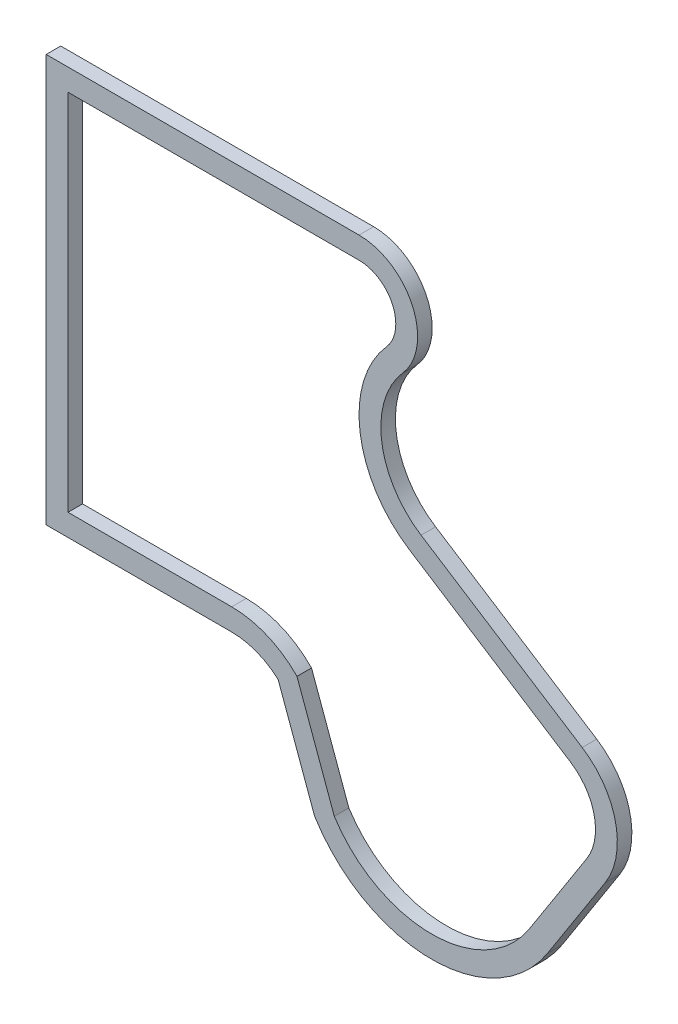
SolidWorks part; units mm, degrees
ref_plane "Front Plane" through (0, 0, 0) normal (0, 0, 1) x (1, 0, 0)
ref_plane "Top Plane" through (0, 0, 0) normal (0, 1, 0) x (1, 0, 0)
ref_plane "Right Plane" through (0, 0, 0) normal (1, 0, 0) x (0, 0, -1)
sketch "Sketch1" plane through (0, 0, 0) normal (0, 0, 1) x (1, 0, 0)
  line L0 (0, 0) -> (0, 127)
  line L1 (0, 127) -> (101.6, 127)
  line L2 (101.6, 127) -> (101.6, 175.337) construction
  line L3 (139.7, 80.3679) -> (194.9929, 30.5819) construction
  line L4 (0, 0) -> (57.15, 0)
  line L5 (79.933, -9.6367) -> (92.964, -45.439)
  line L6 (91.1321, 44.512) -> (91.1321, 7.5666) construction
  line L7 (119.1339, 48.2954) -> (175.3831, 12.2262)
  line L8 (161.036, -45.439) -> (181.1362, -14.0931)
  line L9 (101.6, 114.1681) -> (101.6, 2.8902) construction
  line L10 (-7.62, -7.62) -> (-7.62, 134.62)
  line L11 (-7.62, 134.62) -> (101.6, 134.62)
  line L12 (123.2471, 54.7099) -> (179.4963, 18.6407)
  line L13 (167.4505, -49.5523) -> (187.5507, -18.2063)
  line L14 (73.3702, -13.8849) -> (86.0802, -48.8055)
  line L15 (-7.62, -7.62) -> (57.15, -7.62)
  arc A0 (101.6, 127) -> (111.199, 105.6523) centre (101.6, 114.1681) cw
  arc A1 (111.199, 105.6523) -> (119.1339, 48.2954) centre (139.7, 80.3679) ccw
  arc A2 (57.15, 0) -> (79.933, -9.6367) centre (57.15, -31.75) cw
  arc A3 (92.964, -45.439) -> (161.036, -45.439) centre (127, -23.6138) ccw
  arc A4 (175.3831, 12.2262) -> (181.1362, -14.0931) centre (165.1, -3.81) cw
  arc A5 (101.6, 134.62) -> (116.8992, 100.5954) centre (101.6, 114.1681) cw
  arc A6 (116.8992, 100.5954) -> (123.2471, 54.7099) centre (139.7, 80.3679) ccw
  arc A7 (179.4963, 18.6407) -> (187.5507, -18.2063) centre (165.1, -3.81) cw
  arc A8 (86.0802, -48.8055) -> (167.4505, -49.5523) centre (127, -23.6138) ccw
  arc A9 (57.15, -7.62) -> (73.3702, -13.8849) centre (57.15, -31.75) cw
  dimension "D1" = 101.6
  dimension "D5" = 31.75
  dimension "D11" = 19.05
  dimension "D2" = 127
  dimension "D3" = 139.7
  dimension "D4" = 132
  dimension "D6" = 57.15
  dimension "D7" = 127
  dimension "D8" = 165.1
  dimension "D9" = 20
  dimension "D10" = 38.1
  dimension "D12" = 130.81
  dimension "D13" = 92.964
  dimension "D14" = 7.62
extrude "Boss-Extrude1" add sketch "Sketch1" along normal blind 5.08
